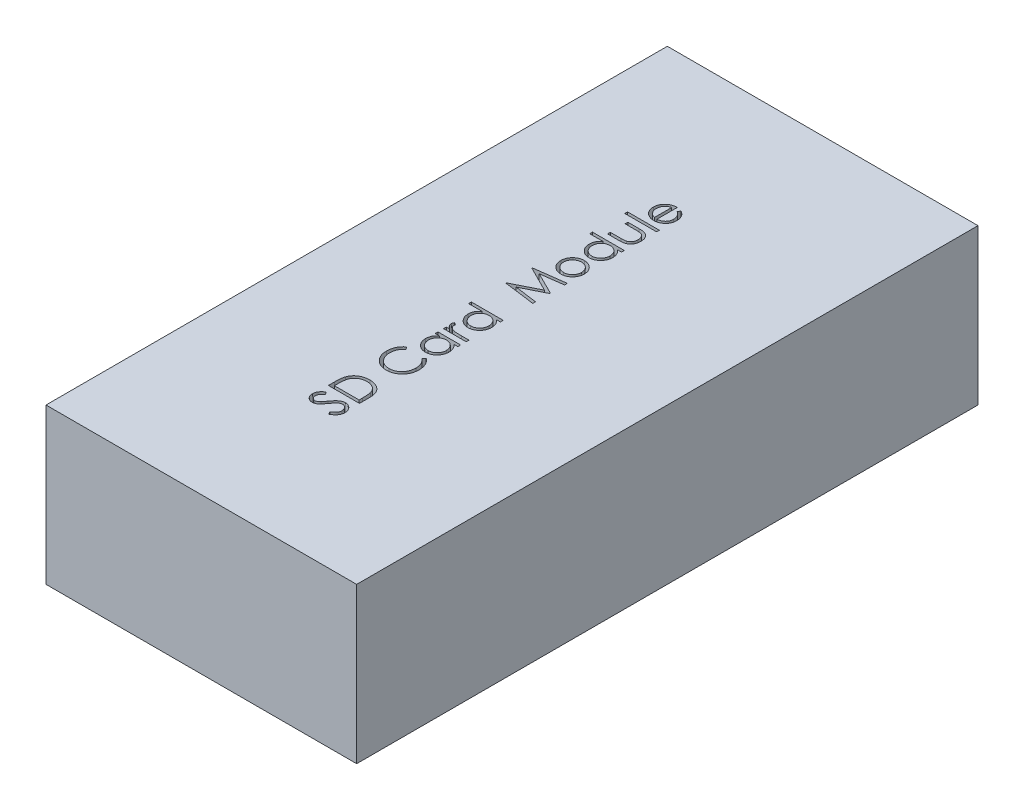
SolidWorks part; units mm, degrees
ref_plane "Front Plane" through (0, 0, 0) normal (0, 0, 1) x (1, 0, 0)
ref_plane "Top Plane" through (0, 0, 0) normal (0, 1, 0) x (1, 0, 0)
ref_plane "Right Plane" through (0, 0, 0) normal (1, 0, 0) x (0, 0, -1)
sketch "Sketch1" plane through (0, 0, 0) normal (0, 1, 0) x (1, 0, 0)
  line L1 (-10, 20) -> (10, 20)
  line L2 (-10, 20) -> (-10, -20)
  line L3 (-10, -20) -> (10, -20)
  line L4 (10, 20) -> (10, -20)
  line L5 (-10, 20) -> (10, -20) construction
  line L6 (-10, -20) -> (10, 20) construction
  point P0 (0, 0)
  dimension "D1" = 20
  dimension "D2" = 40
extrude "Boss-Extrude1" add sketch "Sketch1" along normal blind 10
sketch "Sketch2" plane through (0, 10, 0) normal (0, 1, 0) x (1, 0, 0)
  line L0 (0, -20) -> (0, 20) construction
  line L1 (-10, -20) -> (10, -20) construction
  line L2 (10, 20) -> (-10, 20) construction
  text T0 "SD Card  Module" font "Century Gothic" height 2
extrude "Cut-Extrude1" cut sketch "Sketch2" against normal blind 2
